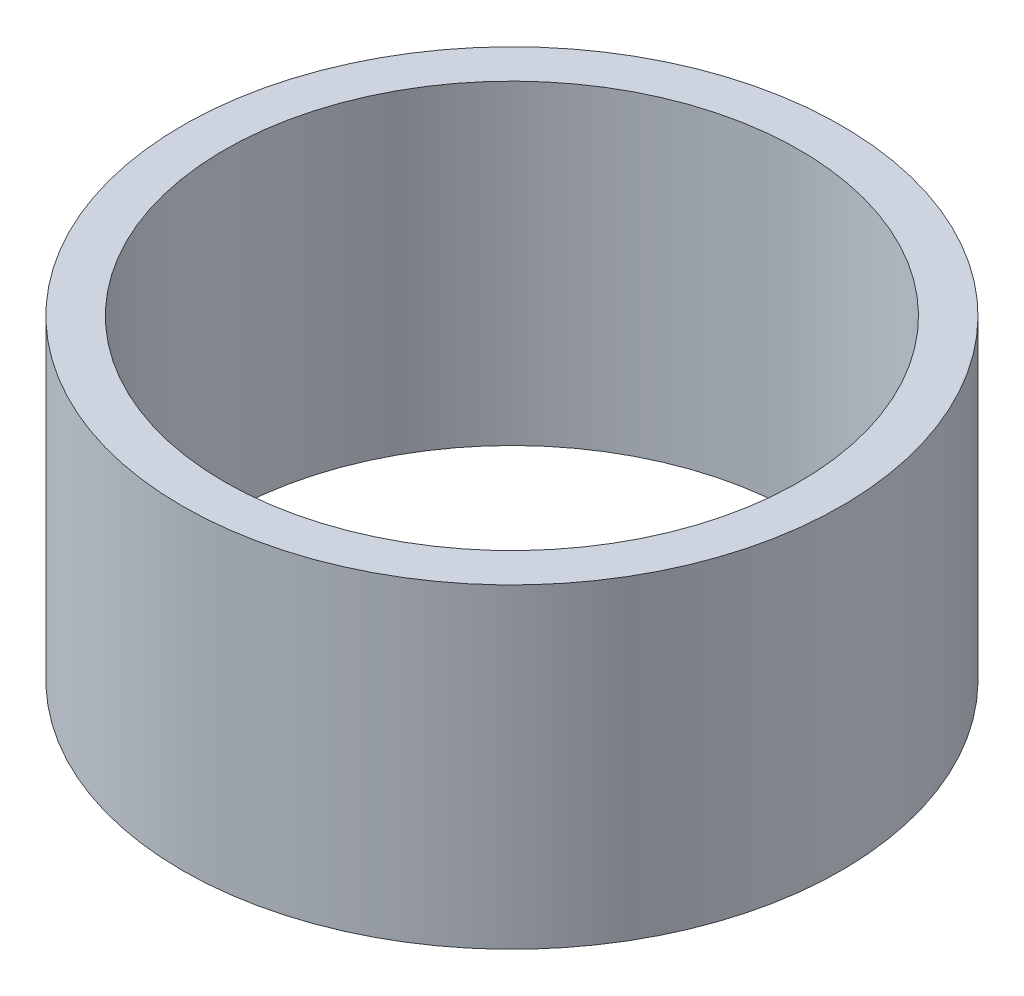
SolidWorks part; units mm, degrees
ref_plane "Face" through (0, 0, 0) normal (0, 0, 1) x (1, 0, 0)
ref_plane "Dessus" through (0, 0, 0) normal (0, 1, 0) x (1, 0, 0)
ref_plane "Droite" through (0, 0, 0) normal (1, 0, 0) x (0, 0, -1)
sketch "Esquisse1" plane through (0, 0, 0) normal (0, 0, 1) x (1, 0, 0)
  line L1 (20.5, 22.5) -> (23.5, 22.5)
  line L2 (20.5, 22.5) -> (20.5, 0)
  line L3 (20.5, 0) -> (23.5, 0)
  line L4 (23.5, 22.5) -> (23.5, 0)
  line L7 (0, 28.1201) -> (0, -6.7506) construction
  line L8 (0, 350) -> (0, -250) construction
  dimension "D1" = 23.5
  dimension "D2" = 3
  dimension "D3" = 22.5
revolve "Révolution1" add sketch "Esquisse1" angle 360 about L7
